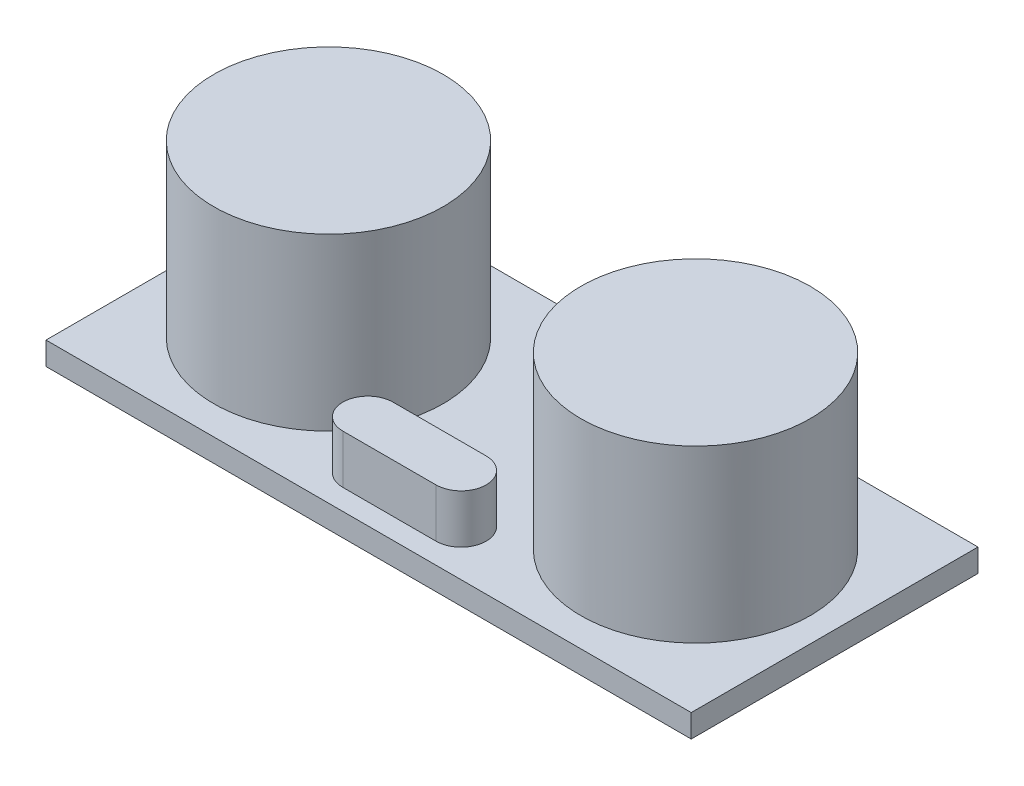
SolidWorks part; units mm, degrees
ref_plane "前视基准面" through (0, 0, 0) normal (0, 0, 1) x (1, 0, 0)
ref_plane "上视基准面" through (0, 0, 0) normal (0, 1, 0) x (1, 0, 0)
ref_plane "右视基准面" through (0, 0, 0) normal (1, 0, 0) x (0, 0, -1)
sketch "草图1" plane through (0, 0, 0) normal (0, 1, 0) x (1, 0, 0)
  line L1 (-22.5, -10) -> (22.5, -10)
  line L2 (-22.5, -10) -> (-22.5, 10)
  line L3 (-22.5, 10) -> (22.5, 10)
  line L4 (22.5, -10) -> (22.5, 10)
  line L5 (-22.5, -10) -> (22.5, 10) construction
  line L6 (-22.5, 10) -> (22.5, -10) construction
  point P0 (0, 0)
  dimension "D1" = 45
  dimension "D2" = 20
extrude "凸台-拉伸1" add sketch "草图1" along normal blind 1.6
sketch "草图2" plane through (0, 1.6, 0) normal (0, 1, 0) x (1, 0, 0)
  line L0 (0, 10) -> (0, -13.5507) construction
  line L1 (22.5, 10) -> (-22.5, 10) construction
  circle A0 centre (12.8, 0) radius 8
  circle A1 centre (-12.8, 0) radius 8
  dimension "D1" = 16
  dimension "D2" = 25.6
extrude "凸台-拉伸2" add sketch "草图2" along normal blind 11.9
sketch "草图3" plane through (0, 1.6, 0) normal (0, 1, 0) x (1, 0, 0)
  line L0 (0, 10) -> (0, -14.4601) construction
  line L1 (22.5, 10) -> (-22.5, 10) construction
  line L2 (-3.25, -6.7988) -> (3.25, -6.7988) construction
  line L3 (-3.25, -5.0488) -> (3.25, -5.0488)
  line L4 (-3.25, -8.5488) -> (3.25, -8.5488)
  arc A0 (-3.25, -5.0488) -> (-3.25, -8.5488) centre (-3.25, -6.7988) ccw
  arc A1 (3.25, -8.5488) -> (3.25, -5.0488) centre (3.25, -6.7988) ccw
  point P7 (0, -6.7988)
  dimension "D1" = 3.5
  dimension "D2" = 6.5
extrude "凸台-拉伸3" add sketch "草图3" along normal blind 3.4
sketch "草图4" plane through (0, 0, 0) normal (0, -1, 0) x (1, 0, 0)
  line L0 (0, -10) -> (0, -6.0023) construction
  line L1 (22.5, -10) -> (-22.5, -10) construction
  line L3 (-5, -7.5) -> (5, -7.5)
  line L4 (-5, -7.5) -> (-5, -10)
  line L5 (-5, -10) -> (5, -10)
  line L6 (5, -7.5) -> (5, -10)
  line L7 (-5, -7.5) -> (5, -10) construction
  line L8 (-5, -10) -> (5, -7.5) construction
  point P5 (0, -8.75)
  dimension "D1" = 2.5
  dimension "D2" = 10
extrude "凸台-拉伸4" add sketch "草图4" along normal blind 10
